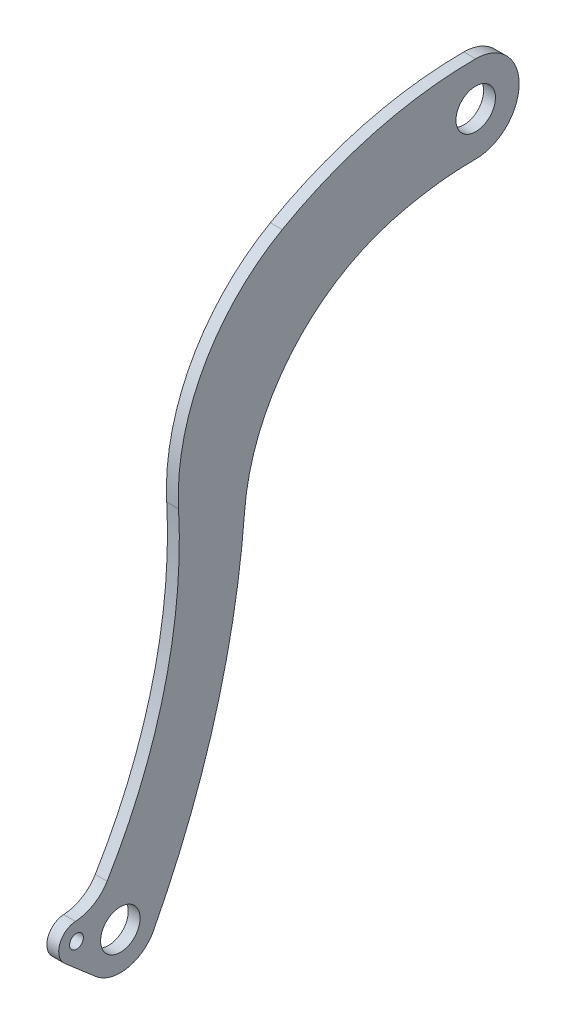
SolidWorks part; units mm, degrees
ref_plane "Front Plane" through (0, 0, 0) normal (0, 0, 1) x (1, 0, 0)
ref_plane "Top Plane" through (0, 0, 0) normal (0, 1, 0) x (1, 0, 0)
ref_plane "Right Plane" through (0, 0, 0) normal (1, 0, 0) x (0, 0, -1)
sketch "Sketch1" plane through (0, 0, 0) normal (1, 0, 0) x (0, 0, -1)
  arc A1 (0, 79) -> (0, 101) centre (0, 90) ccw
  circle A2 centre (0, 0) radius 62.05 construction
  arc A3 (0, 79) -> (-21.0371, 76.1845) centre (0, -1) ccw
  arc A4 (-58.5305, 30.9172) -> (-81.574, -49.3878) centre (-267.4567, 47.41) cw
  arc A5 (0, 101) -> (-49.0141, 88.0273) centre (0, 1.9198) ccw
  arc A6 (-49.0141, 88.0273) -> (-75.2522, 39.8944) centre (-23.2498, 42.7648) ccw
  arc A8 (-21.0371, 76.1845) -> (-58.5305, 30.9172) centre (-7.6035, 26.897) ccw
  arc A9 (-75.2522, 39.8944) -> (-97.7974, -39.5732) centre (-201.9324, 32.9021) cw
  arc A10 (-97.7974, -39.5732) -> (-81.574, -49.3878) centre (-90, -45) ccw
  dimension "D1" = 124.1
  dimension "D2" = 90
  dimension "D3" = 80
  dimension "D4" = 22
  dimension "D5" = 9.5
  dimension "D7" = 90
  dimension "D6" = 45
extrude "Boss-Extrude1" add sketch "Sketch1" along normal mid plane 3
sketch "Sketch2" plane through (1.5, 0, 0) normal (1, 0, 0) x (0, 0, -1)
  circle A0 centre (0, 90) radius 5
  circle A1 centre (-90, -45) radius 5
  dimension "D1" = 10
extrude "Cut-Extrude1" cut sketch "Sketch2" against normal through all
sketch "Sketch4" plane through (1.5, 0, 0) normal (1, 0, 0) x (0, 0, -1)
  line L0 (-104.0468, -45.4315) -> (-96.2039, -52.1945)
  line L1 (-101.1081, -42.0236) -> (-90, -45) construction
  line L2 (-90, -45) -> (-95, -45) construction
  arc A0 (-101.3556, -37.5304) -> (-104.0468, -45.4315) centre (-101.1081, -42.0236) ccw
  circle A1 centre (-101.1081, -42.0236) radius 1.75
  arc A2 (-97.7974, -39.5732) -> (-81.574, -49.3878) centre (-90, -45) ccw construction
  circle A3 centre (-90, -45) radius 5 construction
  arc A4 (-101.3556, -37.5304) -> (-93.3469, -32.7176) centre (-101.9055, -27.5455) ccw
  arc A5 (-97.7974, -39.5732) -> (-75.2522, 39.8944) centre (-201.9324, 32.9021) ccw construction
  arc A6 (-93.3469, -32.7176) -> (-96.2039, -52.1945) centre (-71.6085, -45.8544) ccw
  dimension "D1" = 3.5
  dimension "D2" = 9
  dimension "D5" = 10
  dimension "D3" = 15
  dimension "D4" = 11.5
extrude "Boss-Extrude2" add sketch "Sketch4" against normal up to surface (3 mm away) up to face at (-1.5, 90, -5)
